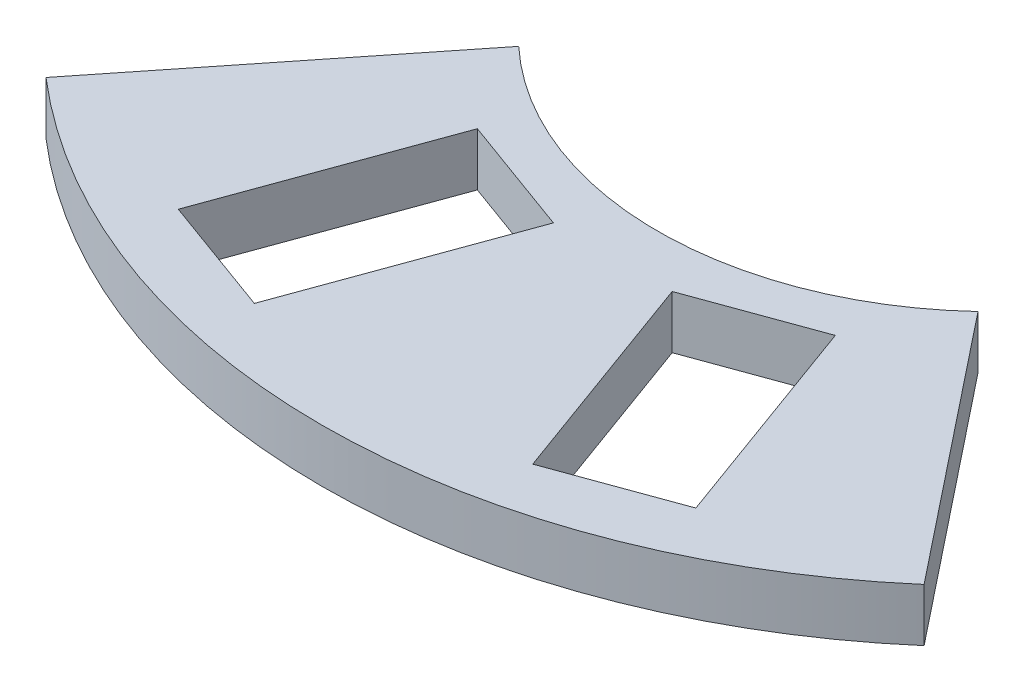
SolidWorks part; units mm, degrees
ref_plane "前视基准面" through (0, 0, 0) normal (0, 0, 1) x (1, 0, 0)
ref_plane "上视基准面" through (0, 0, 0) normal (0, 1, 0) x (1, 0, 0)
ref_plane "右视基准面" through (0, 0, 0) normal (1, 0, 0) x (0, 0, -1)
other "Configuration Table"
sketch "草图1" plane through (0, 0, 0) normal (0, 1, 0) x (1, 0, 0)
  line L0 (0, 0) -> (0, 23.7401) construction
  line L5 (-24.4004, -6.2175) -> (-13.1241, -10.3217)
  line L6 (-24.4004, -6.2175) -> (-16.8759, 14.4558)
  line L7 (-16.8759, 14.4558) -> (-5.5996, 10.3515)
  line L8 (-13.1241, -10.3217) -> (-5.5996, 10.3515)
  line L9 (-24.4004, -6.2175) -> (-5.5996, 10.3515) construction
  line L10 (-16.8759, 14.4558) -> (-13.1241, -10.3217) construction
  line L11 (16.8759, 14.4558) -> (5.5996, 10.3515)
  line L12 (13.1241, -10.3217) -> (5.5996, 10.3515)
  line L13 (24.4004, -6.2175) -> (13.1241, -10.3217)
  line L14 (24.4004, -6.2175) -> (16.8759, 14.4558)
  line L15 (-21.6539, 23.1312) -> (-41.397, -1.6956)
  line L16 (21.6539, 23.1312) -> (41.397, -1.6956)
  arc A0 (21.6539, 23.1312) -> (-21.6539, 23.1312) centre (0, 46.3081) cw
  arc A1 (41.397, -1.6956) -> (-41.397, -1.6956) centre (0, 46.3081) cw
  point P0 (-15, 2.067)
  point P15 (0, 0)
  point P16 (0, 0)
  point P17 (41.397, -1.6956)
  dimension "D1" = 12
  dimension "D2" = 22
  dimension "D3" = 15
extrude "凸台-拉伸1" add sketch "草图1" along normal blind 5
